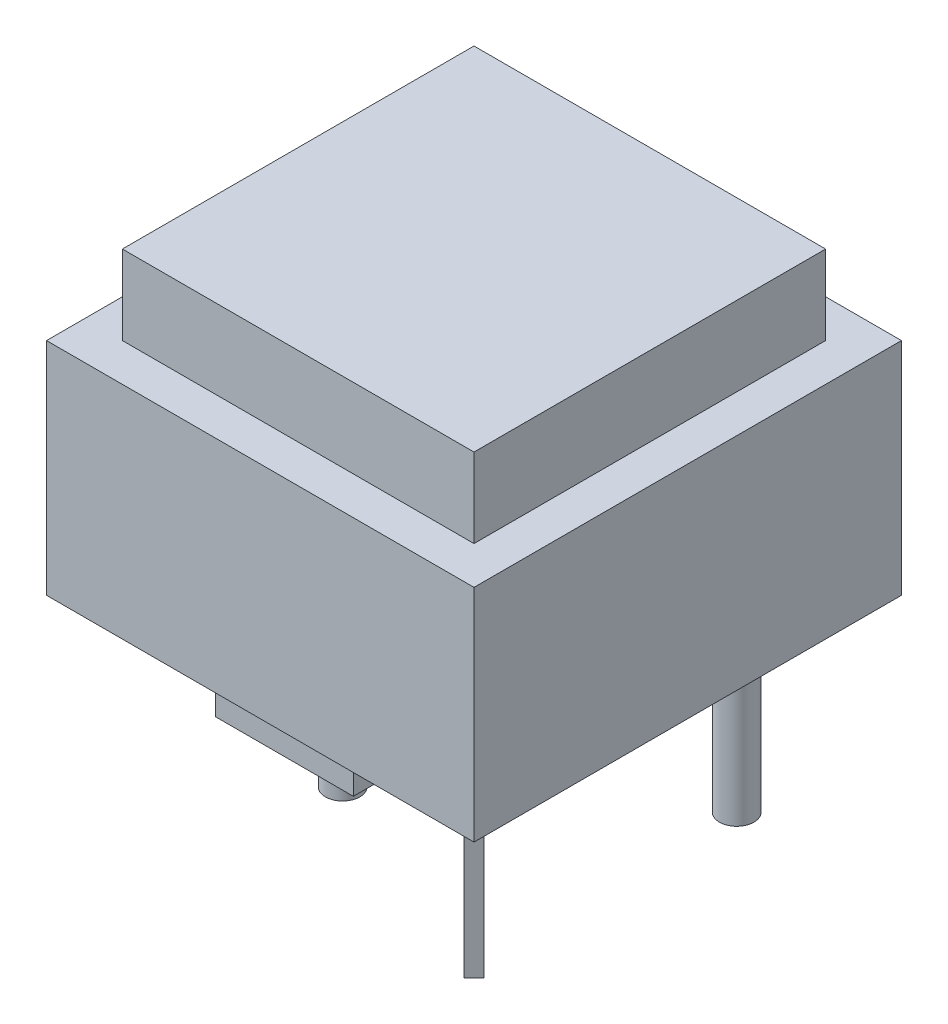
SolidWorks part; units mm, degrees
ref_plane "Front Plane" through (0, 0, 0) normal (0, 0, 1) x (1, 0, 0)
ref_plane "Top Plane" through (0, 0, 0) normal (0, 1, 0) x (1, 0, 0)
ref_plane "Right Plane" through (0, 0, 0) normal (1, 0, 0) x (0, 0, -1)
sketch "Sketch1" plane through (0, 0, 0) normal (0, 1, 0) x (1, 0, 0)
  line L1 (-6.2, -6.2) -> (6.2, -6.2)
  line L2 (-6.2, -6.2) -> (-6.2, 6.2)
  line L3 (-6.2, 6.2) -> (6.2, 6.2)
  line L4 (6.2, -6.2) -> (6.2, 6.2)
  line L5 (-6.2, -6.2) -> (6.2, 6.2) construction
  line L6 (-6.2, 6.2) -> (6.2, -6.2) construction
  point P0 (0, 0)
  dimension "D1" = 12.4
  dimension "D2" = 12.4
extrude "Boss-Extrude1" add sketch "Sketch1" against normal blind 6.4
sketch "Sketch2" plane through (0, 0, 0) normal (0, 1, 0) x (1, 0, 0)
  line L1 (-5.1, -5.1) -> (5.1, -5.1)
  line L2 (-5.1, -5.1) -> (-5.1, 5.1)
  line L3 (-5.1, 5.1) -> (5.1, 5.1)
  line L4 (5.1, -5.1) -> (5.1, 5.1)
  line L5 (-5.1, -5.1) -> (5.1, 5.1) construction
  line L6 (-5.1, 5.1) -> (5.1, -5.1) construction
  point P0 (0, 0)
  dimension "D1" = 10.2
  dimension "D2" = 10.2
extrude "Boss-Extrude2" add sketch "Sketch2" along normal blind 2.3
sketch "Sketch3" plane through (0, -6.4, 0) normal (0, -1, 0) x (1, 0, 0)
  line L0 (-1.4821, -0.775) -> (-0.775, -1.4821)
  line L1 (-1.4821, -0.775) -> (-1.765, -1.0579)
  line L2 (-0.775, -1.4821) -> (-1.0579, -1.765)
  line L3 (-1.765, -1.0579) -> (-1.0579, -1.765)
  line L4 (4.0221, 4.305) -> (3.315, 3.5979)
  line L5 (4.0221, 4.305) -> (4.305, 4.0221)
  line L6 (3.315, 3.5979) -> (3.5979, 3.315)
  line L7 (4.305, 4.0221) -> (3.5979, 3.315)
  line L8 (-6.2, 6.2) -> (6.2, 6.2) construction
  line L9 (3.6686, 3.9514) -> (3.9514, 3.6686)
  line L10 (-1.4114, -1.4114) -> (-1.1286, -1.1286)
  circle A0 centre (3.81, -3.81) radius 0.5
  circle A1 centre (-2.54, 1.27) radius 0.5
  point P14 (3.81, 3.81)
  point P20 (-1.27, -1.27)
  dimension "D12" = 1
  dimension "D13" = 1
  dimension "D1" = 0.4
  dimension "D2" = 1
  dimension "D3" = 45
  dimension "D4" = 3.81
  dimension "D5" = 3.81
  dimension "D6" = 1.27
  dimension "D7" = 1.27
  dimension "D8" = 0.4
  dimension "D9" = 1
  dimension "D10" = 2.54
  dimension "D11" = 2.54
  dimension "D14" = 3.81
  dimension "D15" = 2.54
extrude "Boss-Extrude3" add sketch "Sketch3" along normal blind 5.45 contours A1 | L4 L9 L7 L5 | L9 L4 L6 L7 | A0 | L10 L3 L2 L0 | L3 L10 L0 L1
sketch "Sketch4" plane through (0, -6.4, 0) normal (0, -1, 0) x (1, 0, 0)
  line L7 (-2, -5.5) -> (2, -5.5)
  line L8 (-2, -5.5) -> (-2, -4.5)
  line L9 (-2, -4.5) -> (2, -4.5)
  line L10 (2, -5.5) -> (2, -4.5)
  line L11 (-2, -5.5) -> (2, -4.5) construction
  line L12 (-2, -4.5) -> (2, -5.5) construction
  line L13 (-2, 4.5) -> (2, 4.5)
  line L14 (-2, 4.5) -> (-2, 5.5)
  line L15 (-2, 5.5) -> (2, 5.5)
  line L16 (2, 4.5) -> (2, 5.5)
  line L17 (-2, 4.5) -> (2, 5.5) construction
  line L18 (-2, 5.5) -> (2, 4.5) construction
  point P0 (0, 0)
  point P5 (0, -5)
  point P10 (0, 5)
  dimension "D1" = 5
  dimension "D2" = 5
  dimension "D3" = 4
  dimension "D4" = 1
  dimension "D5" = 4
  dimension "D6" = 1
extrude "Boss-Extrude4" add sketch "Sketch4" along normal blind 1.3
equation "\"D2@Sketch2\"=\"D1@Sketch2\""
equation "\"D2@Sketch4\"=\"D1@Sketch4\""
